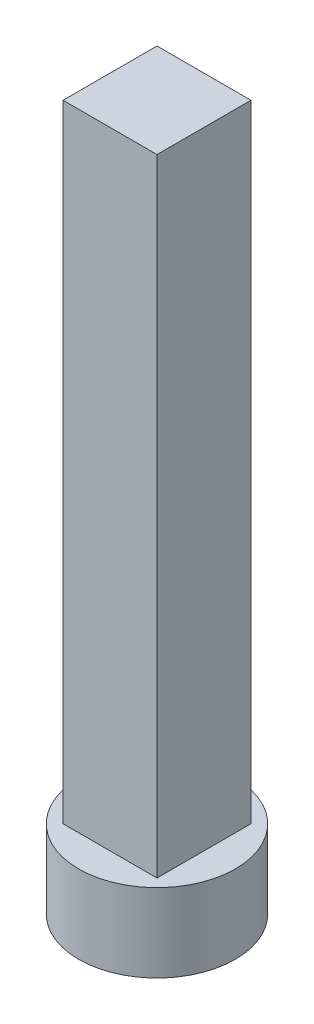
SolidWorks part; units mm, degrees
ref_plane "前视基准面" through (0, 0, 0) normal (0, 0, 1) x (1, 0, 0)
ref_plane "上视基准面" through (0, 0, 0) normal (0, 1, 0) x (1, 0, 0)
ref_plane "右视基准面" through (0, 0, 0) normal (1, 0, 0) x (0, 0, -1)
other "Configuration Table"
sketch "草图1" plane through (0, 0, 0) normal (0, 1, 0) x (1, 0, 0)
  line L1 (-30, 30) -> (30, 30)
  line L2 (-30, 30) -> (-30, -30)
  line L3 (-30, -30) -> (30, -30)
  line L4 (30, 30) -> (30, -30)
  line L5 (-30, 30) -> (30, -30) construction
  line L6 (-30, -30) -> (30, 30) construction
  point P1 (0, 0)
  dimension "D1" = 60
  dimension "D2" = 60
extrude "凸台-拉伸1" add sketch "草图1" along normal blind 400
sketch "草图2" plane through (0, 0, 0) normal (0, -1, 0) x (1, 0, 0)
  circle A0 centre (0, 0) radius 50
  dimension "D1" = 100
extrude "凸台-拉伸2" add sketch "草图2" along normal blind 50
